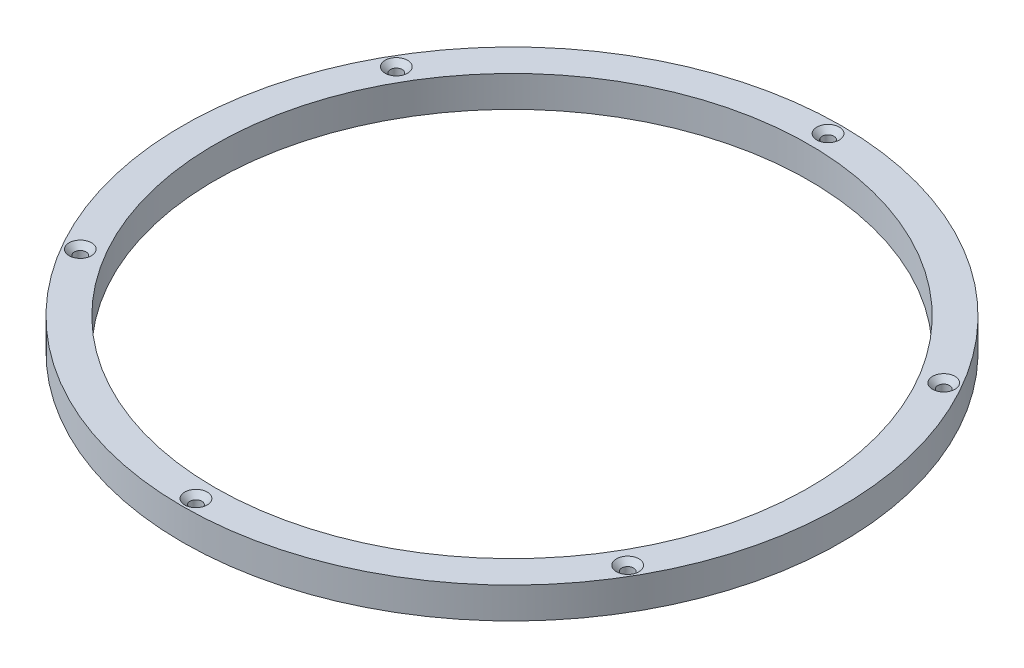
SolidWorks part; units mm, degrees
ref_plane "Front Plane" through (0, 0, 0) normal (0, 0, 1) x (1, 0, 0)
ref_plane "Top Plane" through (0, 0, 0) normal (0, 1, 0) x (1, 0, 0)
ref_plane "Right Plane" through (0, 0, 0) normal (1, 0, 0) x (0, 0, -1)
sketch "Sketch1" plane through (0, 0, 0) normal (0, 1, 0) x (1, 0, 0)
  circle A0 centre (0, 0) radius 145 construction
  circle A1 centre (0, 0) radius 152.5
  circle A2 centre (0, 0) radius 137.5
  dimension "D1" = 290
  dimension "D2" = 7.5
  dimension "D3" = 7.5
extrude "Boss-Extrude1" add sketch "Sketch1" along normal blind 14.4
sketch "Sketch2" plane through (0, 14.4, 0) normal (0, 1, 0) x (1, 0, 0)
  circle A0 centre (0, 0) radius 146.25
  point P3 (0, 146.25)
  point P4 (146.25, 0)
  point P5 (0, -146.25)
  point P6 (-146.25, 0)
  dimension "D1" = 292.5
hole_wizard "CSK for M5 Flat Head Machine Screw1" positions "Sketch3" profile "Sketch4" countersink size "M5" standard "ANSI Metric" end condition through all
sketch "Sketch3" plane through (0, 14.4, 0) normal (0, 1, 0) x (1, 0, 0)
  point P0 (0, 146.25)
sketch "Sketch4" plane through (0, 14.4, -146.25) normal (1, 0, 0) x (0, 0, 1)
  line L0 (0, 0) -> (0, 14.4)
  line L1 (0, 14.4) -> (2.75, 14.4)
  line L2 (2.75, 14.4) -> (2.75, 2.45)
  line L3 (2.75, 2.45) -> (5.2, 0)
  line L5 (5.2, 0) -> (0, 0)
  line L6 (-2.75, 2.45) -> (-5.2, 0) construction
  line L11 (0, -6.35) -> (0, 107.95) construction
  dimension "Thru Hole Dia." = 5.5
  dimension "Thru Hole Depth" = 14.4
  dimension "Near C'Sink Dia." = 10.4
  dimension "Near C'Sink Angle" = 90
pattern_circular "CirPattern1" count 6 over 360 about axis through (0, 0, 0) along (0, 1, 0) of "CSK for M5 Flat Head Machine Screw1"
